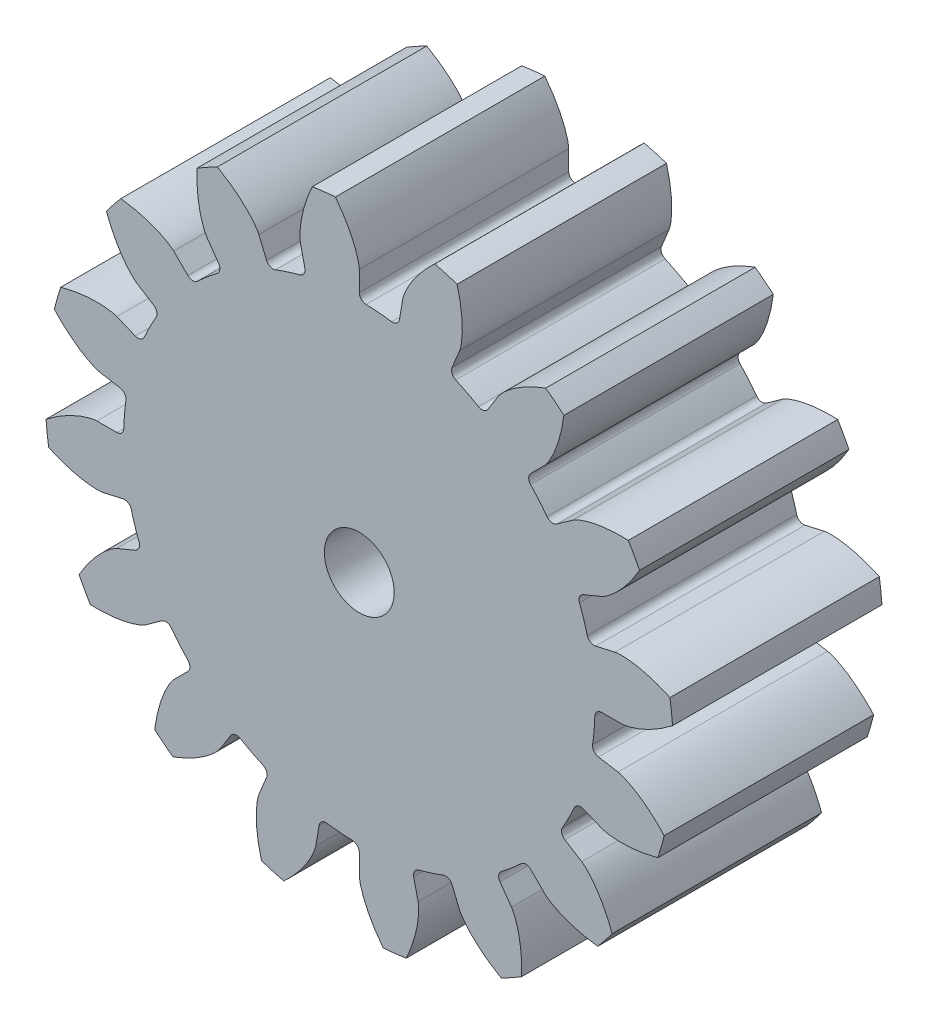
SolidWorks part; units mm, degrees
ref_plane "Front Plane" through (0, 0, 0) normal (0, 0, 1) x (1, 0, 0)
ref_plane "Top Plane" through (0, 0, 0) normal (0, 1, 0) x (1, 0, 0)
ref_plane "Right Plane" through (0, 0, 0) normal (1, 0, 0) x (0, 0, -1)
sketch "Sketch1" plane through (0, 0, 0) normal (0, 0, 1) x (1, 0, 0)
  circle A0 centre (0, 0) radius 4.5
  circle A1 centre (0, 0) radius 0.5
  dimension "D1" = 9
  dimension "D2" = 1
extrude "Boss-Extrude1" add sketch "Sketch1" along normal blind 3
sketch "Sketch3" plane through (0, 0, 0) normal (0, 0, 1) x (1, 0, 0)
  line L0 (3.375, 0) -> (3.7588, 0)
  line L2 (3.3283, -0.5595) -> (3.7068, -0.6231)
  line L3 (0, 0) -> (-4.4844, 0.3743) construction
  circle A0 centre (0, 0) radius 4 construction
  circle A1 centre (0, 0) radius 3.7588 construction
  arc A2 (3.3283, -0.5595) -> (3.375, 0) centre (0, 0) ccw
  circle A3 centre (0, 0) radius 4.5 construction
  spline S0 degree 4 poles (3.7588, 0) (3.7624, 0.0001) (3.7692, 0.0005) (3.7803, 0.0014) (3.8021, 0.0042) (3.8267, 0.0084) (3.8544, 0.0143) (3.884, 0.0218) (3.9091, 0.0289) (3.9342, 0.0366) (3.959, 0.0448) (3.9889, 0.0554) (4.0246, 0.0691) (4.066, 0.0865) (4.1126, 0.1078) (4.1597, 0.1312) (4.2056, 0.1556) (4.2515, 0.1818) (4.2956, 0.2083) (4.3408, 0.2374) (4.3823, 0.2651) (4.4282, 0.2979) (4.465, 0.3248) (4.5129, 0.3622) (4.5409, 0.3848) (4.5735, 0.4119) (4.5878, 0.4243) (4.5966, 0.4319) knots 0 0 0 0 0 0.015084 0.028532 0.04661 0.092111 0.119476 0.146842 0.174209 0.201575 0.228941 0.256307 0.307035 0.361767 0.4165 0.471232 0.525964 0.580697 0.635429 0.690161 0.744894 0.799626 0.854358 0.909091 0.954545 1 1 1 1 1 construction
  spline S1 degree 4 poles (3.7588, 0) (3.7624, 0.0001) (3.7692, 0.0005) (3.7803, 0.0014) (3.8021, 0.0042) (3.8267, 0.0084) (3.8544, 0.0143) (3.884, 0.0218) (3.9091, 0.0289) (3.9342, 0.0366) (3.959, 0.0448) (3.9889, 0.0554) (4.0246, 0.0691) (4.066, 0.0865) (4.1126, 0.1078) (4.1597, 0.1312) (4.2056, 0.1556) (4.2515, 0.1818) (4.2956, 0.2083) (4.3408, 0.2374) (4.3823, 0.2651) (4.4282, 0.2979) (4.465, 0.3248) (4.5025, 0.3541) (4.5206, 0.3686) (4.5299, 0.376) knots 0 0 0 0 0 0.015084 0.028532 0.04661 0.092111 0.119476 0.146842 0.174209 0.201575 0.228941 0.256307 0.307035 0.361767 0.4165 0.471232 0.525964 0.580697 0.635429 0.690161 0.744894 0.799626 0.854358 0.909091 0.909091 0.909091 0.909091 0.909091
  spline S2 degree 4 poles (3.7068, -0.6231) (3.7103, -0.6237) (3.717, -0.6253) (3.7277, -0.6281) (3.7488, -0.6344) (3.7724, -0.6427) (3.7987, -0.6531) (3.8266, -0.6653) (3.8503, -0.6765) (3.8737, -0.6882) (3.8968, -0.7005) (3.9245, -0.7159) (3.9575, -0.7353) (3.9954, -0.7593) (4.0379, -0.7881) (4.0804, -0.8189) (4.1216, -0.8506) (4.1625, -0.8841) (4.2016, -0.9175) (4.2414, -0.9537) (4.2777, -0.9879) (4.3175, -1.0278) (4.3494, -1.0605) (4.3904, -1.1053) (4.4143, -1.1323) (4.4419, -1.1644) (4.454, -1.1789) (4.4614, -1.1879) knots 0 0 0 0 0 0.015084 0.028532 0.04661 0.092111 0.119476 0.146842 0.174209 0.201575 0.228941 0.256307 0.307035 0.361767 0.4165 0.471232 0.525964 0.580697 0.635429 0.690161 0.744894 0.799626 0.854358 0.909091 0.954545 1 1 1 1 1 construction
  spline S3 degree 4 poles (3.7068, -0.6231) (3.7103, -0.6237) (3.717, -0.6253) (3.7277, -0.6281) (3.7488, -0.6344) (3.7724, -0.6427) (3.7987, -0.6531) (3.8266, -0.6653) (3.8503, -0.6765) (3.8737, -0.6882) (3.8968, -0.7005) (3.9245, -0.7159) (3.9575, -0.7353) (3.9954, -0.7593) (4.0379, -0.7881) (4.0804, -0.8189) (4.1216, -0.8506) (4.1625, -0.8841) (4.2016, -0.9175) (4.2414, -0.9537) (4.2777, -0.9879) (4.3175, -1.0278) (4.3494, -1.0605) (4.3815, -1.0956) (4.397, -1.1129) (4.4049, -1.1218) knots 0 0 0 0 0 0.015084 0.028532 0.04661 0.092111 0.119476 0.146842 0.174209 0.201575 0.228941 0.256307 0.307035 0.361767 0.4165 0.471232 0.525964 0.580697 0.635429 0.690161 0.744894 0.799626 0.854358 0.909091 0.909091 0.909091 0.909091 0.909091
  point P5 (3.375, 0)
  point P11 (3.3283, -0.5595)
  dimension "D1" = 8
  dimension "D2" = 7.5175
  dimension "D3" = 6.75
  dimension "D4" = 4.771
  dimension "D5" = 4.771
extrude "Cut-Extrude1" cut sketch "Sketch3" against normal through all and the other way through all
fillet "Fillet1" radius 0.1 1 edges at (3.3283, -0.5595, 1.5)
fillet "Fillet2" radius 0.1 1 edges at (3.375, 0, 1.5)
pattern_circular "CirPattern14" count 16 over 360 about axis through (0, 0, 3) along (0, 0, -1) of "Cut-Extrude1", "Fillet1", "Fillet2"
equation "\"P\"= 2'Diametral Pitch"
equation "\"N\"= 16'Number of teeth"
equation "\"phi\"= 20deg'pressure angle"
equation "\"a\"= 1 / \"P\"'addendum"
equation "\"b\"= 1.25 / \"P\"'dedendum"
equation "\"c\"= \"b\" - \"a\"'clearance"
equation "\"dp\"= \"N\" / \"P\"'pitch circle diameter"
equation "\"db\"= \"dp\" * cos ( \"phi\" )'base circle diameter"
equation "\"D1@Sketch1\"= \"dp\" + 2 * \"a\"'Addendum circle diameter"
equation "\"D1@Sketch3\"= \"dp\"'pitch circle"
equation "\"D2@Sketch3\"= \"db\" 'base circle"
equation "\"D3@Sketch3\" = \"dp\" - 2 * \"b\"'dedendum circle"
equation "\"alpha\"= sqr ( \"dp\" ^ 2 - \"db\" ^ 2 ) / \"db\" * 180 / pi - \"phi\"'alpha (deg)"
equation "\"beta\"= ( 360 / ( 4 * \"N\" ) - \"alpha\" ) * 2"
equation "\"D4@Sketch3\"= 360 / ( 4 * \"N\" ) - \"alpha\""
equation "\"D5@Sketch3\"= 360 / ( 4 * \"N\" ) - \"alpha\""
